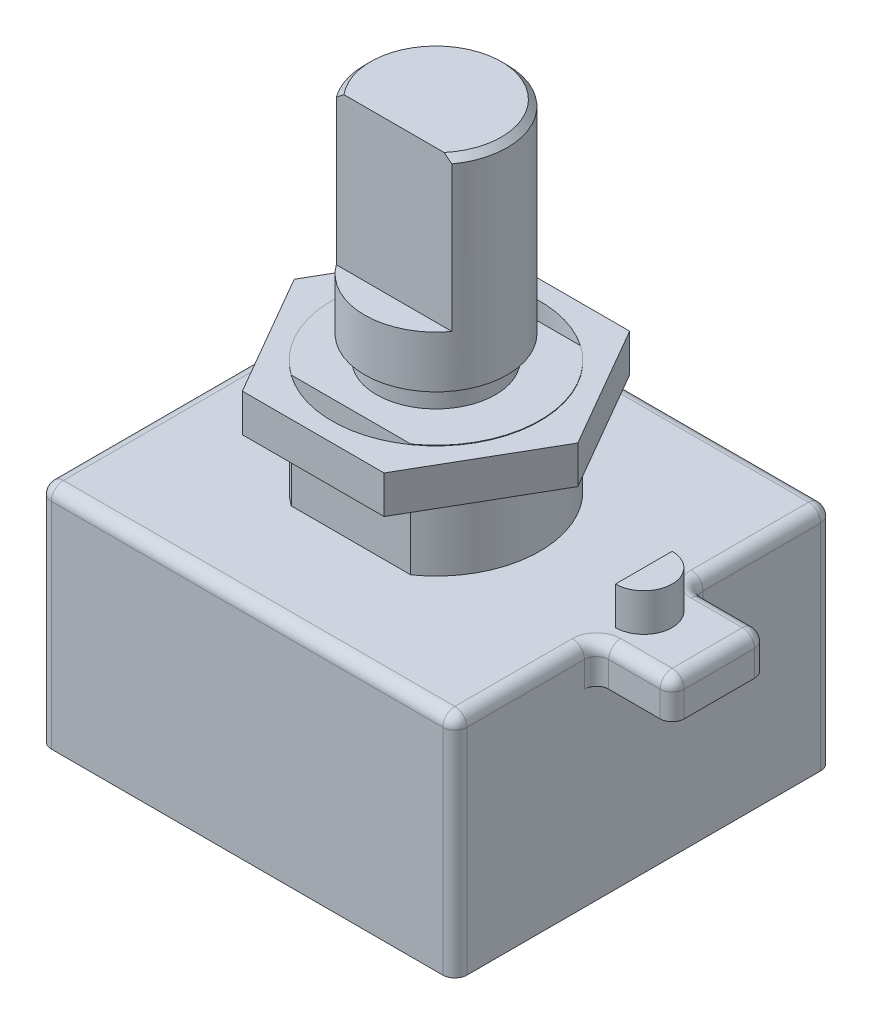
SolidWorks part; units mm, degrees
ref_plane "Front Plane" through (0, 0, 0) normal (0, 0, 1) x (1, 0, 0)
ref_plane "Top Plane" through (0, 0, 0) normal (0, 1, 0) x (1, 0, 0)
ref_plane "Right Plane" through (0, 0, 0) normal (1, 0, 0) x (0, 0, -1)
sketch "Sketch1" plane through (0, 0, 0) normal (0, 1, 0) x (1, 0, 0)
  line L1 (-8.7312, -7.9375) -> (8.7313, -7.9375)
  line L2 (-8.7312, -7.9375) -> (-8.7312, 7.9375)
  line L3 (-8.7312, 7.9375) -> (8.7313, 7.9375)
  line L4 (8.7313, -7.9375) -> (8.7313, 7.9375)
  line L5 (-8.7312, -7.9375) -> (8.7313, 7.9375) construction
  line L6 (-8.7312, 7.9375) -> (8.7313, -7.9375) construction
  point P0 (0, 0)
  dimension "D1" = 15.875
  dimension "D2" = 17.4625
extrude "Boss-Extrude1" add sketch "Sketch1" along normal blind 9.525
sketch "Sketch2" plane through (0, 9.525, 0) normal (0, 1, 0) x (1, 0, 0)
  circle A0 centre (0, 0) radius 4.3656
  dimension "D1" = 8.7312
extrude "Boss-Extrude2" add sketch "Sketch2" along normal blind 4.7625
sketch "Sketch3" plane through (0, 14.2875, 0) normal (0, 1, 0) x (1, 0, 0)
  line L0 (0, 0) -> (-13.1182, 0) construction
  line L1 (-7.8581, 0) -> (7.8581, 0) construction
  line L2 (-2.5101, -3.5719) -> (2.5101, -3.5719)
  line L3 (-2.5101, 3.5719) -> (2.5101, 3.5719)
  circle A0 centre (0, 0) radius 4.3656 construction
  arc A1 (2.5101, -3.5719) -> (-2.5101, -3.5719) centre (0, 0) cw
  arc A2 (2.5101, 3.5719) -> (-2.5101, 3.5719) centre (0, 0) ccw
  dimension "D1" = 7.1437
extrude "Cut-Extrude1" cut sketch "Sketch3" against normal up to surface (4.7625 mm away) up to face at (0, 9.525, 0)
sketch "Sketch4" plane through (0, 14.2875, 0) normal (0, 1, 0) x (1, 0, 0)
  line L1 (2.9788, 5.1594) -> (-2.9788, 5.1594)
  line L2 (-2.9788, 5.1594) -> (-5.9575, 0)
  line L3 (-5.9575, 0) -> (-2.9788, -5.1594)
  line L4 (-2.9788, -5.1594) -> (2.9788, -5.1594)
  line L5 (2.9788, -5.1594) -> (5.9575, 0)
  line L6 (5.9575, 0) -> (2.9788, 5.1594)
  circle A0 centre (0, 0) radius 4.3656
  arc A1 (-2.5101, 3.5719) -> (-2.5101, -3.5719) centre (0, 0) ccw construction
  circle A2 centre (0, 0) radius 5.1594 construction
  dimension "D1" = 10.3187
extrude "Boss-Extrude3" add sketch "Sketch4" against normal blind 1.5875 from offset 0.0254 separate body offset against normal yes
sketch "Sketch5" plane through (0, 0, 0) normal (1, 0, 0) x (0, 0, -1)
  line L0 (0, 14.2621) -> (0, -9.6578) construction
  line L1 (0, 7.8581) -> (0, -7.8581) construction
  line L2 (-2.5, 14.2621) -> (-2.5, 15.2621)
  line L3 (-5.1594, 14.2621) -> (0, 14.2621) construction
  line L4 (-2.5, 15.2621) -> (-3, 15.2621)
  line L5 (-3, 15.2621) -> (-3, 23.7871)
  line L6 (-3, 23.7871) -> (0, 23.7871)
  line L7 (0, 23.7871) -> (0, 14.2621)
  line L8 (0, 14.2621) -> (-2.5, 14.2621)
  line L9 (0, 14.2621) -> (5.1594, 14.2621) construction
  dimension "D1" = 6
  dimension "D2" = 2.5
  dimension "D3" = 1
  dimension "D4" = 9.525
revolve "Revolve1" add sketch "Sketch5" angle 360 about L0
sketch "Sketch6" plane through (0, 0, 0) normal (1, 0, 0) x (0, 0, -1)
  line L0 (3, 23.7871) -> (-3, 23.7871) construction
  line L1 (-1.7625, 23.7871) -> (-1.7625, 17.4371)
  line L2 (-1.7625, 17.4371) -> (-3, 17.4371)
  line L3 (-3, 23.7871) -> (-3, 15.2621) construction
  line L4 (-3, 17.4371) -> (-3, 23.7871)
  line L5 (-3, 23.7871) -> (-1.7625, 23.7871)
  line L6 (3, 15.2621) -> (3, 23.7871) construction
  dimension "D1" = 4.7625
  dimension "D2" = 6.35
extrude "Cut-Extrude2" cut sketch "Sketch6" against normal up to next and the other way up to next
chamfer "Chamfer1" distance 0.254 angle 45 1 edges at (0, 23.7871, -3)
sketch "Sketch7" plane through (0, 9.525, 0) normal (0, 1, 0) x (1, 0, 0)
  line L0 (8.7313, -7.9375) -> (8.7313, 7.9375) construction
  line L1 (8.7313, 1.9844) -> (11.9063, 1.9844)
  line L2 (8.7313, 1.9844) -> (8.7313, -1.9844)
  line L3 (8.7313, -1.9844) -> (11.9063, -1.9844)
  line L4 (11.9063, 1.9844) -> (11.9063, -1.9844)
  line L5 (0, 0) -> (-12.95, 0) construction
  line L6 (-9.6044, 0) -> (9.6044, 0) construction
  dimension "D1" = 3.9688
  dimension "D2" = 3.175
extrude "Boss-Extrude4" add sketch "Sketch7" against normal blind 1.5875
sketch "Sketch8" plane through (0, 9.525, 0) normal (0, 1, 0) x (1, 0, 0)
  line L0 (8.7313, 1.1906) -> (8.7313, -1.1906)
  line L1 (-13.0829, 0) -> (13.0829, 0) construction
  line L2 (-8.7312, 7.9375) -> (-8.7312, -7.9375) construction
  arc A0 (8.7313, -1.1906) -> (8.7313, 1.1906) centre (8.7313, 0) ccw
  dimension "D1" = 2.3813
  dimension "D2" = 17.4625
extrude "Boss-Extrude5" add sketch "Sketch8" along normal blind 1.5875
fillet "Fillet1" radius 0.508 16 edges at (0, 9.525, -7.9375) (11.9063, 9.525, 0) (0, 9.525, 7.9375) (-8.7312, 9.525, 0) (-8.7312, 4.7625, -7.9375) (-8.7312, 4.7625, 7.9375) (8.7313, 4.7625, 7.9375) (8.7313, 4.7625, -7.9375) (11.9063, 8.7312, -1.9844) (11.9063, 8.7312, 1.9844)
